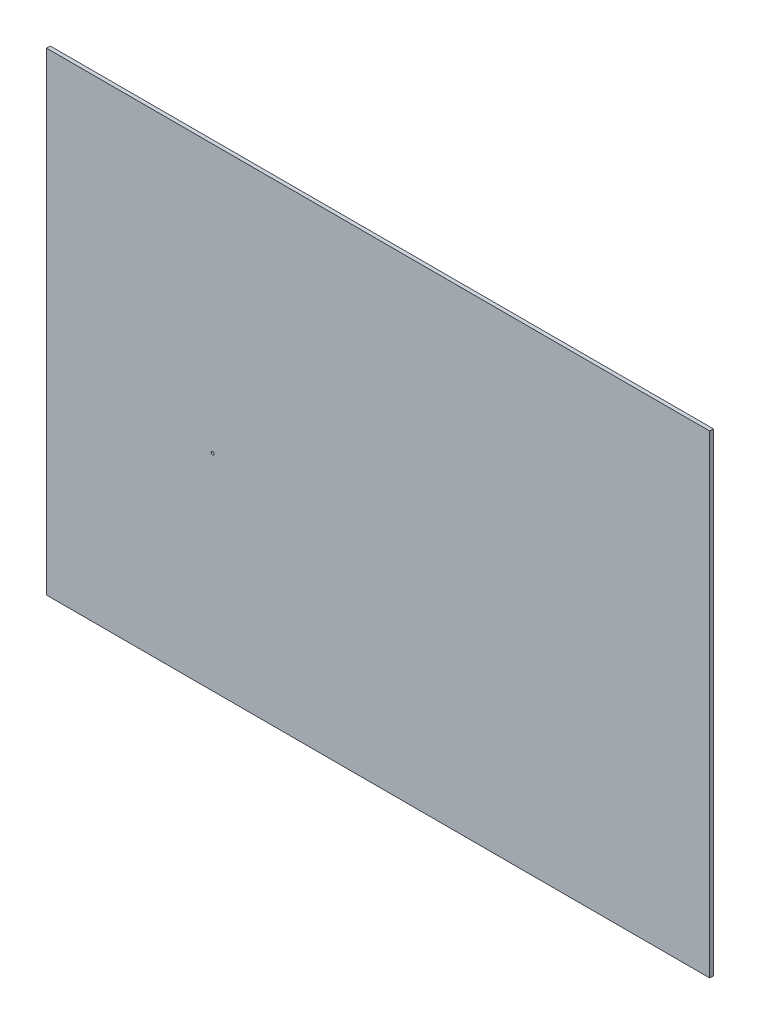
SolidWorks part; units mm, degrees
ref_plane "Спереди" through (0, 0, 0) normal (0, 0, 1) x (1, 0, 0)
ref_plane "Сверху" through (0, 0, 0) normal (0, 1, 0) x (1, 0, 0)
ref_plane "Справа" through (0, 0, 0) normal (1, 0, 0) x (0, 0, -1)
sketch "Эскиз1" plane through (0, 0, 0) normal (0, 0, 1) x (1, 0, 0)
  line L4 (25.4, 25.4) -> (95.4, 25.4)
  line L5 (95.4, 25.4) -> (95.4, 75.4)
  line L6 (95.4, 75.4) -> (25.4, 75.4)
  line L7 (25.4, 75.4) -> (25.4, 25.4)
extrude "Board" add sketch "Эскиз1" along normal blind 0.3912
sketch "Эскиз2" plane through (0, 0, 0.3912) normal (0, 0, 1) x (1, 0, 0)
  circle A0 centre (42.926, 47.128) radius 0.15
extrude "Вырез-Вытянуть1" cut sketch "Эскиз2" against normal blind 0.3912
